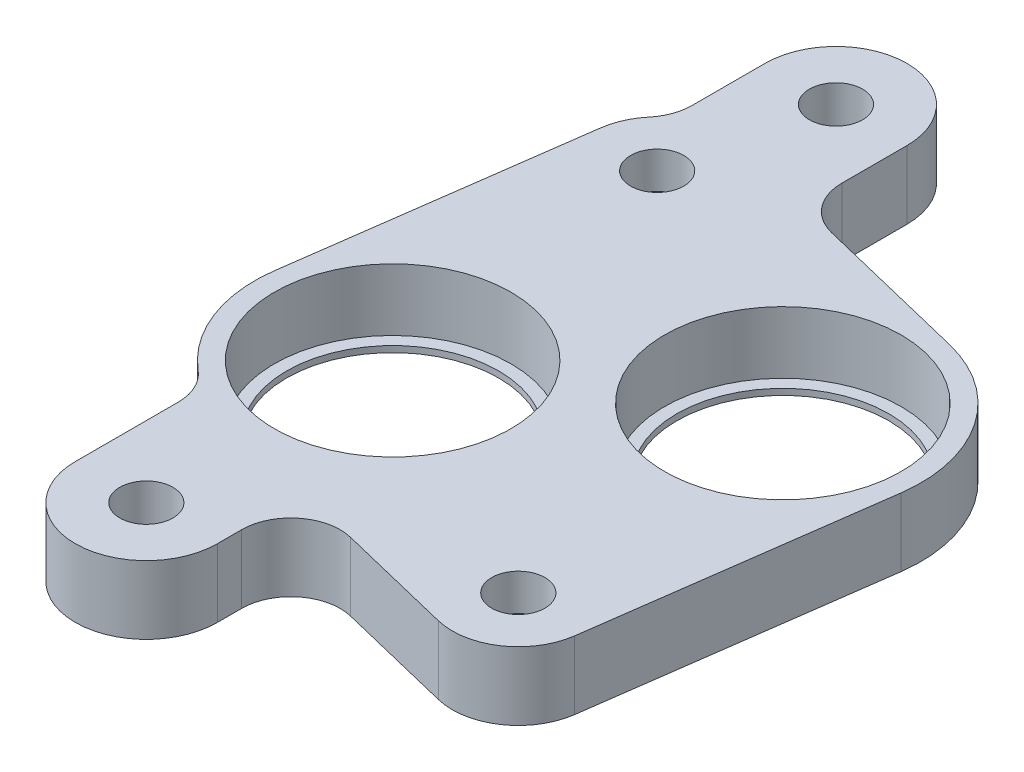
SolidWorks part; units mm, degrees
ref_plane "Front Plane" through (0, 0, 0) normal (0, 0, 1) x (1, 0, 0)
ref_plane "Top Plane" through (0, 0, 0) normal (0, 1, 0) x (1, 0, 0)
ref_plane "Right Plane" through (0, 0, 0) normal (1, 0, 0) x (0, 0, -1)
sketch "Sketch1" plane through (0, 0, 0) normal (0, -1, 0) x (-1, 0, 0)
  line L0 (-14.9625, 10.1854) -> (-17.0236, -8.9252) construction
  line L1 (-17.0236, -8.9252) -> (0, 0) construction
  line L2 (0, 0) -> (2.0611, 19.1106) construction
  line L3 (2.0611, 19.1106) -> (-14.9625, 10.1854) construction
  line L4 (-8.5895, 16.3936) -> (3.7867, 3.6887) construction
  line L5 (-8.5895, 16.3936) -> (-6.3152, 18.609) construction
  line L6 (-6.3152, 18.609) -> (6.061, 5.9042) construction
  line L7 (6.061, 5.9042) -> (3.7867, 3.6887) construction
  line L8 (7.627, 0) -> (8.897, 0) construction
  line L9 (3.7756, 19.1106) -> (6.3156, 19.1106) construction
  line L10 (-18.7381, -8.9252) -> (-21.2781, -8.9252) construction
  line L11 (-21.2385, -9.5041) -> (-23.7767, 8.9747)
  line L12 (-17.0682, 18.8296) -> (1.0542, 23.2442)
  line L13 (6.276, 19.6895) -> (8.8142, 1.2107)
  line L14 (-16.0167, -13.0588) -> (2.1057, -8.6442)
  circle A0 centre (-14.9625, 10.1854) radius 7.627
  circle A1 centre (0, 0) radius 7.627
  circle A3 centre (2.0611, 19.1106) radius 1.7145
  circle A4 centre (-17.0236, -8.9252) radius 1.7145
  circle A5 centre (-14.9625, 10.1854) radius 7.5 construction
  circle A6 centre (0, 0) radius 5.2864 construction
  circle A9 centre (-14.9625, 10.1854) radius 8.897 construction
  circle A10 centre (2.0611, 19.1106) radius 4.2545 construction
  circle A11 centre (0, 0) radius 8.897 construction
  circle A12 centre (-17.0236, -8.9252) radius 4.2545 construction
  arc A13 (-17.0682, 18.8296) -> (-23.7767, 8.9747) centre (-14.9625, 10.1854) ccw
  arc A14 (-21.2385, -9.5041) -> (-16.0167, -13.0588) centre (-17.0236, -8.9252) ccw
  arc A15 (8.8142, 1.2107) -> (2.1057, -8.6442) centre (0, 0) cw
  arc A16 (6.276, 19.6895) -> (1.0542, 23.2442) centre (2.0611, 19.1106) ccw
  dimension "D1" = 0.127
  dimension "D2" = 3.429
  dimension "D3" = 3.175
  dimension "D4" = 6.35
  dimension "D6" = 2.54
  dimension "D5" = 1.27
extrude "Boss-Extrude1" add sketch "Sketch1" against normal up to surface (4 mm away)
sketch "Sketch2" plane through (0, 0, 0) normal (0, -1, 0) x (1, 0, 0)
  line L4 (16.0167, 13.0588) -> (-2.1057, 8.6442)
  line L5 (-8.8142, -1.2107) -> (-6.276, -19.6895)
  line L6 (-1.0542, -23.2442) -> (17.0682, -18.8296)
  line L7 (23.7767, -8.9747) -> (21.2385, 9.5041)
  line L8 (16.0167, 13.0588) -> (-2.1057, 8.6442)
  line L9 (-8.8142, -1.2107) -> (-6.276, -19.6895)
  line L10 (-1.0542, -23.2442) -> (17.0682, -18.8296)
  line L11 (23.7767, -8.9747) -> (21.2385, 9.5041)
  circle A0 centre (14.9625, -10.1854) radius 6.8332
  circle A1 centre (0, 0) radius 6.8332
  circle A2 centre (14.9625, -10.1854) radius 7.627 construction
  arc A4 (21.2385, 9.5041) -> (16.0167, 13.0588) centre (17.0236, 8.9252) ccw
  arc A5 (-2.1057, 8.6442) -> (-8.8142, -1.2107) centre (0, 0) ccw
  arc A6 (-6.276, -19.6895) -> (-1.0542, -23.2442) centre (-2.0611, -19.1106) ccw
  arc A7 (17.0682, -18.8296) -> (23.7767, -8.9747) centre (14.9625, -10.1854) ccw
  arc A8 (21.2385, 9.5041) -> (16.0167, 13.0588) centre (17.0236, 8.9252) ccw
  arc A9 (-2.1057, 8.6442) -> (-8.8142, -1.2107) centre (0, 0) ccw
  arc A10 (-6.276, -19.6895) -> (-1.0542, -23.2442) centre (-2.0611, -19.1106) ccw
  arc A11 (17.0682, -18.8296) -> (23.7767, -8.9747) centre (14.9625, -10.1854) ccw
  dimension "D2" = 0.7937
  dimension "D1" = 0
extrude "Boss-Extrude2" add sketch "Sketch2" along normal blind 0.3969
sketch "Sketch3" plane through (0, -0.3969, 0) normal (0, -1, 0) x (1, 0, 0)
  circle A0 centre (17.0236, 8.9252) radius 2.794
  circle A1 centre (-2.0611, -19.1106) radius 2.794
  dimension "D1" = 5.588
extrude "Cut-Extrude1" cut sketch "Sketch3" against normal blind 2.032
sketch "Sketch6" plane through (0, -0.3969, 0) normal (0, -1, 0) x (1, 0, 0)
  line L1 (-4.581, 7.627) -> (4.581, 7.627) construction
  line L2 (-4.581, 7.627) -> (-4.581, 15.875)
  line L4 (4.581, 7.627) -> (4.581, 15.875) construction
  line L6 (-4.581, -22.5385) -> (-4.581, -28.575)
  line L7 (-4.581, -28.575) -> (4.581, -28.575) construction
  line L8 (4.581, -21.8715) -> (4.581, -28.575)
  line L9 (16.0167, 13.0588) -> (-2.1057, 8.6442) construction
  line L10 (-2.1057, 8.6442) -> (4.581, 10.2731)
  line L11 (4.581, 10.2731) -> (4.581, 15.875)
  line L12 (-1.0542, -23.2442) -> (17.0682, -18.8296) construction
  line L13 (-1.0542, -23.2442) -> (4.581, -21.8715)
  arc A0 (-2.1057, 8.6442) -> (-8.8142, -1.2107) centre (0, 0) ccw construction
  circle A1 centre (0, 0) radius 7.627 construction
  arc A2 (4.581, 15.875) -> (-4.581, 15.875) centre (0, 15.875) ccw
  circle A3 centre (0, 15.875) radius 1.7145
  arc A4 (-4.581, -28.575) -> (4.581, -28.575) centre (0, -28.575) ccw
  circle A5 centre (0, -28.575) radius 1.7145
  arc A7 (-4.581, 7.627) -> (-2.1057, 8.6442) centre (0, 0) cw
  arc A8 (-6.276, -19.6895) -> (-1.0542, -23.2442) centre (-2.0611, -19.1106) ccw construction
  arc A9 (-1.0542, -23.2442) -> (-4.581, -22.5385) centre (-2.0611, -19.1106) cw
  point P7 (0, 7.627)
  dimension "D1" = 3.429
  dimension "D2" = 15.875
  dimension "D3" = 28.575
extrude "Boss-Extrude5" add sketch "Sketch6" against normal up to surface (4.3969 mm away) up to face at (7.4813, 4, -5.0927)
fillet "Fillet1" radius 3.175 4 edges at (4.581, 1.8016, 10.2731) (-4.581, 1.8016, 7.627) (4.581, 1.8016, -21.8715) (-4.581, 1.8016, -22.5385)
